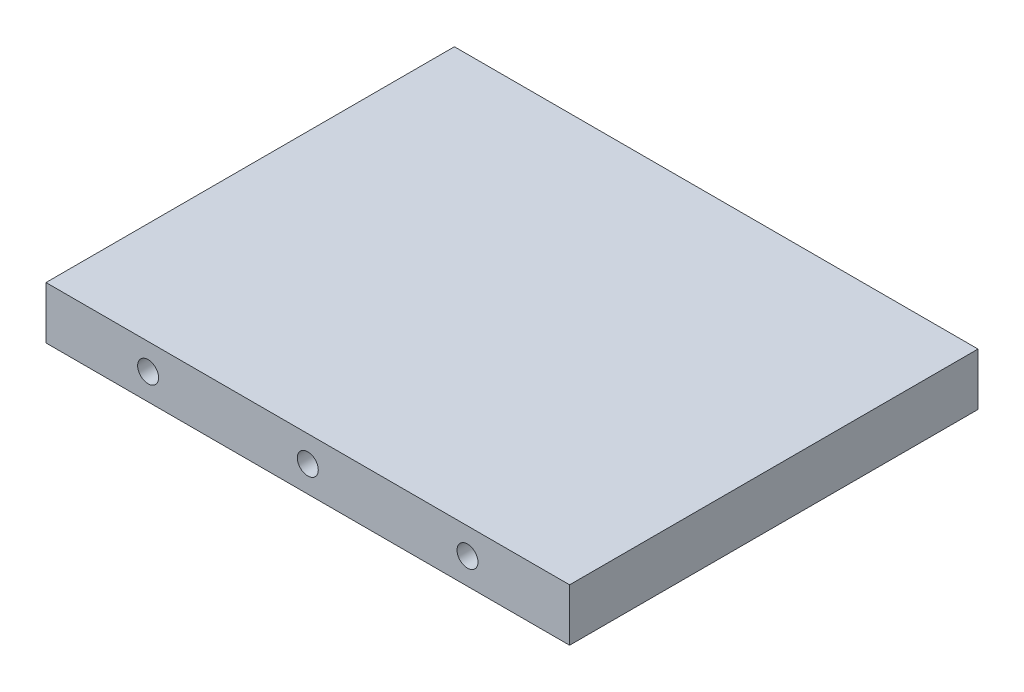
SolidWorks part; units mm, degrees
ref_plane "Piano frontale" through (0, 0, 0) normal (0, 0, 1) x (1, 0, 0)
ref_plane "Piano superiore" through (0, 0, 0) normal (0, 1, 0) x (1, 0, 0)
ref_plane "Piano destro" through (0, 0, 0) normal (1, 0, 0) x (0, 0, -1)
sketch "Schizzo2" plane through (0, 0, 0) normal (0, 0, 1) x (1, 0, 0)
  line L1 (0, 0) -> (100, 0)
  line L2 (0, 0) -> (0, 10)
  line L3 (0, 10) -> (100, 10)
  line L4 (100, 0) -> (100, 10)
  dimension "D1" = 10
  dimension "D2" = 100
extrude "Estrusione-Estrusione1" add sketch "Schizzo2" against normal blind 78
sketch "Schizzo3" plane through (0, 0, 0) normal (0, 0, 1) x (1, 0, 0)
  line L0 (0, 5) -> (100, 5) construction
  line L1 (0, 10) -> (0, 0) construction
  line L2 (100, 0) -> (100, 10) construction
  line L3 (50, 10) -> (50, 0) construction
  line L4 (100, 10) -> (0, 10) construction
  line L5 (0, 0) -> (100, 0) construction
  circle A0 centre (19.5, 5) radius 2
  circle A1 centre (50, 5) radius 2
  circle A2 centre (80.5, 5) radius 2
  dimension "D2" = 4
  dimension "D3" = 4
  dimension "D1" = 30.5
extrude "Taglio-Estrusione1" cut sketch "Schizzo3" against normal blind 15
sketch "Schizzo4" plane through (0, 0, -78) normal (0, 0, -1) x (-1, 0, 0)
  line L0 (-100, 5) -> (0, 5) construction
  line L1 (-100, 0) -> (-100, 10) construction
  line L2 (0, 10) -> (0, 0) construction
  line L3 (-50, 10) -> (-50, 0) construction
  line L4 (-100, 10) -> (0, 10) construction
  line L5 (0, 0) -> (-100, 0) construction
  circle A0 centre (-80.5, 5) radius 2
  circle A1 centre (-50, 5) radius 2
  circle A2 centre (-19.5, 5) radius 2
  dimension "D2" = 4
  dimension "D3" = 4
  dimension "D1" = 30.5
extrude "Taglio-Estrusione2" cut sketch "Schizzo4" against normal blind 15
